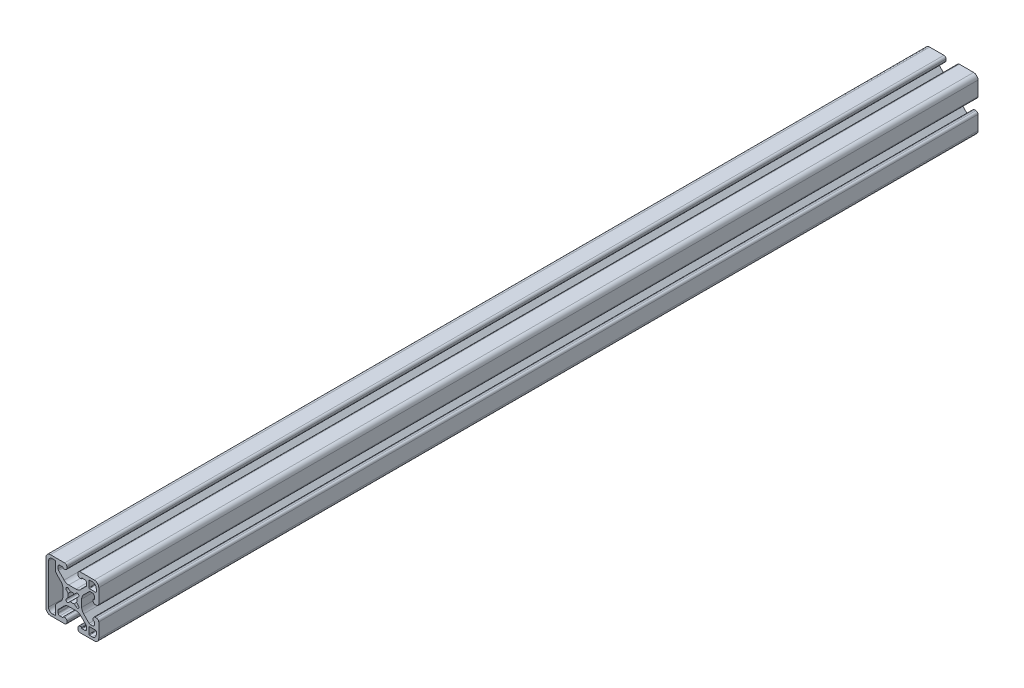
SolidWorks part; units mm, degrees
ref_plane "Front Plane" through (0, 0, 0) normal (0, 0, 1) x (1, 0, 0)
ref_plane "Top Plane" through (0, 0, 0) normal (0, 1, 0) x (1, 0, 0)
ref_plane "Right Plane" through (0, 0, 0) normal (1, 0, 0) x (0, 0, -1)
ref_plane "Plane1" through (0, 0, -533.4) normal (0, 0, -1) x (-1, 0, 0)
sketch "Sketch1" plane through (0, 0, -533.4) normal (0, 0, -1) x (-1, 0, 0)
  line L0 (17.2463, 14.4523) -> (17.2463, -14.4523)
  line L1 (14.4523, -17.2463) -> (12.5803, -17.2463)
  line L2 (12.1993, -16.8653) -> (12.1993, -11.3592)
  line L3 (11.2694, -9.1141) -> (8.2569, -6.1016)
  line L4 (6.8657, -2.743) -> (6.8657, 2.743)
  line L5 (8.2569, 6.1016) -> (11.2694, 9.1141)
  line L6 (12.1993, 11.3592) -> (12.1993, 16.8653)
  line L7 (12.5803, 17.2463) -> (14.4523, 17.2463)
  line L8 (3.0179, -1.4014) -> (4.3433, -2.7269)
  line L9 (2.7269, -4.3433) -> (1.4014, -3.0179)
  line L10 (-1.4014, -3.0179) -> (-2.7269, -4.3433)
  line L11 (-4.3433, -2.7269) -> (-3.0179, -1.4014)
  line L12 (-3.0179, 1.4014) -> (-4.3433, 2.7269)
  line L13 (-2.7269, 4.3433) -> (-1.4014, 3.0179)
  line L14 (1.4014, 3.0179) -> (2.7269, 4.3433)
  line L15 (4.3433, 2.7269) -> (3.0179, 1.4014)
  line L16 (-11.8618, 16.8656) -> (-11.8618, 12.2428)
  line L17 (-12.2428, 11.8618) -> (-16.8656, 11.8618)
  line L18 (-17.2466, 12.2428) -> (-17.2466, 14.4526)
  line L19 (-14.4526, 17.2466) -> (-12.2428, 17.2466)
  line L20 (-11.8618, -12.2428) -> (-11.8618, -16.8656)
  line L21 (-12.2428, -17.2466) -> (-14.4526, -17.2466)
  line L22 (-17.2466, -14.4526) -> (-17.2466, -12.2428)
  line L23 (-16.8656, -11.8618) -> (-12.2428, -11.8618)
  line L24 (19.05, -15.875) -> (19.05, 15.875)
  line L25 (15.875, 19.05) -> (5.5795, 19.05)
  line L26 (4.0057, 17.5302) -> (3.9737, 16.6158)
  line L27 (5.5476, 14.986) -> (6.2683, 14.986)
  line L28 (6.6491, 15.3537) -> (6.6527, 15.4565)
  line L29 (7.0335, 15.8242) -> (9.017, 15.8242)
  line L30 (10.287, 14.5542) -> (10.287, 12.9683)
  line L31 (9.915, 12.0703) -> (5.9669, 8.1222)
  line L32 (2.6083, 6.731) -> (-2.6083, 6.731)
  line L33 (-5.9669, 8.1222) -> (-9.915, 12.0703)
  line L34 (-10.287, 12.9683) -> (-10.287, 14.5542)
  line L35 (-9.017, 15.8242) -> (-7.0335, 15.8242)
  line L36 (-6.6527, 15.4565) -> (-6.6491, 15.3537)
  line L37 (-6.2683, 14.986) -> (-5.5476, 14.986)
  line L38 (-3.9737, 16.6158) -> (-4.0057, 17.5302)
  line L39 (-5.5795, 19.05) -> (-15.875, 19.05)
  line L40 (-19.05, 15.875) -> (-19.05, 5.5795)
  line L41 (-17.5302, 4.0057) -> (-16.6158, 3.9737)
  line L42 (-14.986, 5.5476) -> (-14.986, 6.2683)
  line L43 (-15.3537, 6.6491) -> (-15.4565, 6.6527)
  line L44 (-15.8242, 7.0335) -> (-15.8242, 9.017)
  line L45 (-14.5542, 10.287) -> (-12.9683, 10.287)
  line L46 (-12.0703, 9.915) -> (-8.1222, 5.9669)
  line L47 (-6.731, 2.6083) -> (-6.731, -2.6083)
  line L48 (-8.1222, -5.9669) -> (-12.0703, -9.915)
  line L49 (-12.9683, -10.287) -> (-14.5542, -10.287)
  line L50 (-15.8242, -9.017) -> (-15.8242, -7.0335)
  line L51 (-15.4565, -6.6527) -> (-15.3537, -6.6491)
  line L52 (-14.986, -6.2683) -> (-14.986, -5.5476)
  line L53 (-16.6158, -3.9737) -> (-17.5302, -4.0057)
  line L54 (-19.05, -5.5795) -> (-19.05, -15.875)
  line L55 (-15.875, -19.05) -> (-5.5795, -19.05)
  line L56 (-4.0057, -17.5302) -> (-3.9737, -16.6158)
  line L57 (-5.5476, -14.986) -> (-6.2683, -14.986)
  line L58 (-6.6491, -15.3537) -> (-6.6527, -15.4565)
  line L59 (-7.0335, -15.8242) -> (-9.017, -15.8242)
  line L60 (-10.287, -14.5542) -> (-10.287, -12.9683)
  line L61 (-9.915, -12.0703) -> (-5.9669, -8.1222)
  line L62 (-2.6083, -6.731) -> (2.6083, -6.731)
  line L63 (5.9669, -8.1222) -> (9.915, -12.0703)
  line L64 (10.287, -12.9683) -> (10.287, -14.5542)
  line L65 (9.017, -15.8242) -> (7.0335, -15.8242)
  line L66 (6.6527, -15.4565) -> (6.6491, -15.3537)
  line L67 (6.2683, -14.986) -> (5.5476, -14.986)
  line L68 (3.9737, -16.6158) -> (4.0057, -17.5302)
  line L69 (5.5795, -19.05) -> (15.875, -19.05)
  arc A0 (17.2463, -14.4523) -> (14.4523, -17.2463) centre (14.4523, -14.4523) cw
  arc A1 (12.5803, -17.2463) -> (12.1993, -16.8653) centre (12.5803, -16.8653) cw
  arc A2 (12.1993, -11.3592) -> (11.2694, -9.1141) centre (9.0243, -11.3592) ccw
  arc A3 (8.2569, -6.1016) -> (6.8657, -2.743) centre (11.6155, -2.743) cw
  arc A4 (6.8657, 2.743) -> (8.2569, 6.1016) centre (11.6155, 2.743) cw
  arc A5 (11.2694, 9.1141) -> (12.1993, 11.3592) centre (9.0243, 11.3592) ccw
  arc A6 (12.1993, 16.8653) -> (12.5803, 17.2463) centre (12.5803, 16.8653) cw
  arc A7 (14.4523, 17.2463) -> (17.2463, 14.4523) centre (14.4523, 14.4523) cw
  arc A8 (4.3433, -2.7269) -> (2.7269, -4.3433) centre (3.5351, -3.5351) cw
  arc A9 (1.4014, -3.0179) -> (-1.4014, -3.0179) centre (0, 0) cw
  arc A10 (-2.7269, -4.3433) -> (-4.3433, -2.7269) centre (-3.5351, -3.5351) cw
  arc A11 (-3.0179, -1.4014) -> (-3.0179, 1.4014) centre (0, 0) cw
  arc A12 (-4.3433, 2.7269) -> (-2.7269, 4.3433) centre (-3.5351, 3.5351) cw
  arc A13 (-1.4014, 3.0179) -> (1.4014, 3.0179) centre (0, 0) cw
  arc A14 (2.7269, 4.3433) -> (4.3433, 2.7269) centre (3.5351, 3.5351) cw
  arc A15 (3.0179, 1.4014) -> (3.0179, -1.4014) centre (0, 0) cw
  arc A16 (-11.8618, 12.2428) -> (-12.2428, 11.8618) centre (-12.2428, 12.2428) cw
  arc A17 (-16.8656, 11.8618) -> (-17.2466, 12.2428) centre (-16.8656, 12.2428) cw
  arc A18 (-17.2466, 14.4526) -> (-14.4526, 17.2466) centre (-14.4526, 14.4526) cw
  arc A19 (-12.2428, 17.2466) -> (-11.8618, 16.8656) centre (-12.2428, 16.8656) cw
  arc A20 (-12.2428, -11.8618) -> (-11.8618, -12.2428) centre (-12.2428, -12.2428) cw
  arc A21 (-11.8618, -16.8656) -> (-12.2428, -17.2466) centre (-12.2428, -16.8656) cw
  arc A22 (-14.4526, -17.2466) -> (-17.2466, -14.4526) centre (-14.4526, -14.4526) cw
  arc A23 (-17.2466, -12.2428) -> (-16.8656, -11.8618) centre (-16.8656, -12.2428) cw
  arc A24 (19.05, 15.875) -> (15.875, 19.05) centre (15.875, 15.875) ccw
  arc A25 (5.5795, 19.05) -> (4.0057, 17.5302) centre (5.5795, 17.4752) ccw
  arc A26 (3.9737, 16.6158) -> (5.5476, 14.986) centre (5.5476, 16.5608) ccw
  arc A27 (6.2683, 14.986) -> (6.6491, 15.3537) centre (6.2683, 15.367) ccw
  arc A28 (6.6527, 15.4565) -> (7.0335, 15.8242) centre (7.0335, 15.4432) cw
  arc A29 (9.017, 15.8242) -> (10.287, 14.5542) centre (9.017, 14.5542) cw
  arc A30 (10.287, 12.9683) -> (9.915, 12.0703) centre (9.017, 12.9683) cw
  arc A31 (5.9669, 8.1222) -> (2.6083, 6.731) centre (2.6083, 11.4808) cw
  arc A32 (-2.6083, 6.731) -> (-5.9669, 8.1222) centre (-2.6083, 11.4808) cw
  arc A33 (-9.915, 12.0703) -> (-10.287, 12.9683) centre (-9.017, 12.9683) cw
  arc A34 (-10.287, 14.5542) -> (-9.017, 15.8242) centre (-9.017, 14.5542) cw
  arc A35 (-7.0335, 15.8242) -> (-6.6527, 15.4565) centre (-7.0335, 15.4432) cw
  arc A36 (-6.6491, 15.3537) -> (-6.2683, 14.986) centre (-6.2683, 15.367) ccw
  arc A37 (-5.5476, 14.986) -> (-3.9737, 16.6158) centre (-5.5476, 16.5608) ccw
  arc A38 (-4.0057, 17.5302) -> (-5.5795, 19.05) centre (-5.5795, 17.4752) ccw
  arc A39 (-15.875, 19.05) -> (-19.05, 15.875) centre (-15.875, 15.875) ccw
  arc A40 (-19.05, 5.5795) -> (-17.5302, 4.0057) centre (-17.4752, 5.5795) ccw
  arc A41 (-16.6158, 3.9737) -> (-14.986, 5.5476) centre (-16.5608, 5.5476) ccw
  arc A42 (-14.986, 6.2683) -> (-15.3537, 6.6491) centre (-15.367, 6.2683) ccw
  arc A43 (-15.4565, 6.6527) -> (-15.8242, 7.0335) centre (-15.4432, 7.0335) cw
  arc A44 (-15.8242, 9.017) -> (-14.5542, 10.287) centre (-14.5542, 9.017) cw
  arc A45 (-12.9683, 10.287) -> (-12.0703, 9.915) centre (-12.9683, 9.017) cw
  arc A46 (-8.1222, 5.9669) -> (-6.731, 2.6083) centre (-11.4808, 2.6083) cw
  arc A47 (-6.731, -2.6083) -> (-8.1222, -5.9669) centre (-11.4808, -2.6083) cw
  arc A48 (-12.0703, -9.915) -> (-12.9683, -10.287) centre (-12.9683, -9.017) cw
  arc A49 (-14.5542, -10.287) -> (-15.8242, -9.017) centre (-14.5542, -9.017) cw
  arc A50 (-15.8242, -7.0335) -> (-15.4565, -6.6527) centre (-15.4432, -7.0335) cw
  arc A51 (-15.3537, -6.6491) -> (-14.986, -6.2683) centre (-15.367, -6.2683) ccw
  arc A52 (-14.986, -5.5476) -> (-16.6158, -3.9737) centre (-16.5608, -5.5476) ccw
  arc A53 (-17.5302, -4.0057) -> (-19.05, -5.5795) centre (-17.4752, -5.5795) ccw
  arc A54 (-19.05, -15.875) -> (-15.875, -19.05) centre (-15.875, -15.875) ccw
  arc A55 (-5.5795, -19.05) -> (-4.0057, -17.5302) centre (-5.5795, -17.4752) ccw
  arc A56 (-3.9737, -16.6158) -> (-5.5476, -14.986) centre (-5.5476, -16.5608) ccw
  arc A57 (-6.2683, -14.986) -> (-6.6491, -15.3537) centre (-6.2683, -15.367) ccw
  arc A58 (-6.6527, -15.4565) -> (-7.0335, -15.8242) centre (-7.0335, -15.4432) cw
  arc A59 (-9.017, -15.8242) -> (-10.287, -14.5542) centre (-9.017, -14.5542) cw
  arc A60 (-10.287, -12.9683) -> (-9.915, -12.0703) centre (-9.017, -12.9683) cw
  arc A61 (-5.9669, -8.1222) -> (-2.6083, -6.731) centre (-2.6083, -11.4808) cw
  arc A62 (2.6083, -6.731) -> (5.9669, -8.1222) centre (2.6083, -11.4808) cw
  arc A63 (9.915, -12.0703) -> (10.287, -12.9683) centre (9.017, -12.9683) cw
  arc A64 (10.287, -14.5542) -> (9.017, -15.8242) centre (9.017, -14.5542) cw
  arc A65 (7.0335, -15.8242) -> (6.6527, -15.4565) centre (7.0335, -15.4432) cw
  arc A66 (6.6491, -15.3537) -> (6.2683, -14.986) centre (6.2683, -15.367) ccw
  arc A67 (5.5476, -14.986) -> (3.9737, -16.6158) centre (5.5476, -16.5608) ccw
  arc A68 (4.0057, -17.5302) -> (5.5795, -19.05) centre (5.5795, -17.4752) ccw
  arc A69 (15.875, -19.05) -> (19.05, -15.875) centre (15.875, -15.875) ccw
extrude "Boss-Extrude1" add sketch "Sketch1" against normal blind 635
